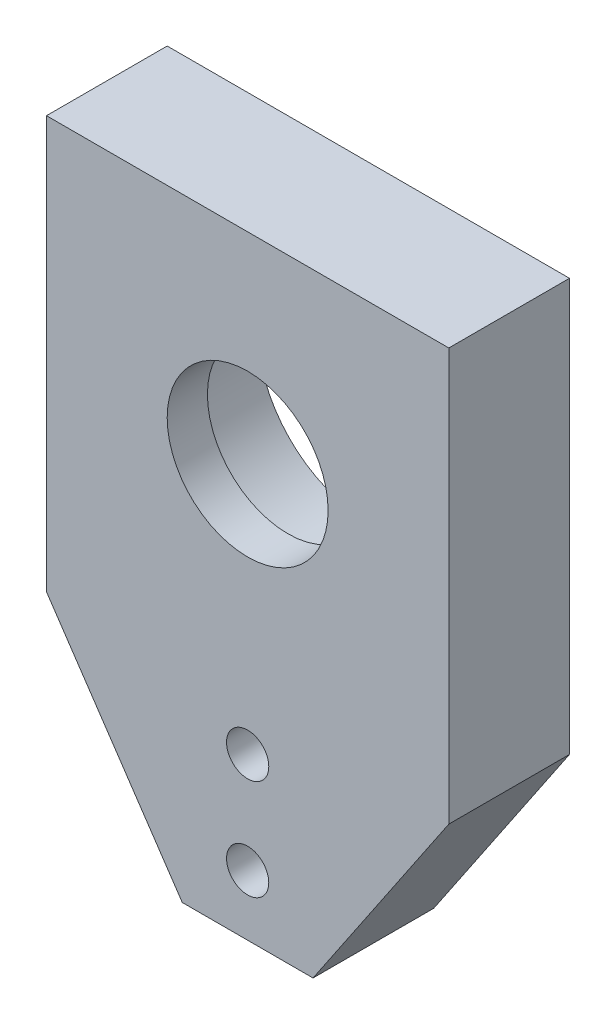
SolidWorks part; units mm, degrees
ref_plane "Front Plane" through (0, 0, 0) normal (0, 0, 1) x (1, 0, 0)
ref_plane "Top Plane" through (0, 0, 0) normal (0, 1, 0) x (1, 0, 0)
ref_plane "Right Plane" through (0, 0, 0) normal (1, 0, 0) x (0, 0, -1)
sketch "Sketch1" plane through (0, 0, 0) normal (0, 0, 1) x (1, 0, 0)
  line L0 (0, 0) -> (0, -35) construction
  line L1 (-20, 20) -> (20, 20)
  line L2 (20, 20) -> (20, -21)
  line L3 (20, -21) -> (6.5, -41)
  line L4 (6.5, -41) -> (-6.5, -41)
  line L5 (-6.5, -41) -> (-20, -21)
  line L6 (-20, -21) -> (-20, 20)
  line L7 (-20, -21) -> (20, -21) construction
  circle A0 centre (0, 0) radius 11
  circle A1 centre (0, -35) radius 2.1
  circle A2 centre (0, -25) radius 2.1
  dimension "D1" = 4.2
  dimension "D2" = 4.2
  dimension "D5" = 22
  dimension "D3" = 10
  dimension "D4" = 25
  dimension "D6" = 13
  dimension "D7" = 6.5
  dimension "D8" = 6
  dimension "D9" = 40
  dimension "D10" = 20
  dimension "D11" = 20
  dimension "D12" = 20
extrude "Boss-Extrude1" add sketch "Sketch1" along normal blind 8
sketch "Sketch2" plane through (0, 0, 8) normal (0, 0, 1) x (1, 0, 0)
  line L6 (20, -21) -> (20, 20)
  line L7 (20, 20) -> (-20, 20)
  line L8 (-20, 20) -> (-20, -21)
  line L9 (-20, -21) -> (-6.5, -41)
  line L10 (-6.5, -41) -> (6.5, -41)
  line L11 (6.5, -41) -> (20, -21)
  line L12 (20, -21) -> (20, 20)
  line L13 (20, 20) -> (-20, 20)
  line L14 (-20, 20) -> (-20, -21)
  line L15 (-20, -21) -> (-6.5, -41)
  line L16 (-6.5, -41) -> (6.5, -41)
  line L17 (6.5, -41) -> (20, -21)
  circle A0 centre (0, 0) radius 8
  circle A1 centre (0, -35) radius 2.1 construction
  circle A2 centre (0, -25) radius 2.1 construction
  circle A3 centre (0, -35) radius 2.1
  circle A4 centre (0, -25) radius 2.1
  dimension "D2" = 16
  dimension "D1" = 0
extrude "Boss-Extrude2" add sketch "Sketch2" along normal blind 4
equation "\"D7@Sketch1\"=\"D6@Sketch1\"/2"
equation "\"D10@Sketch1\"=\"D9@Sketch1\"/2"
